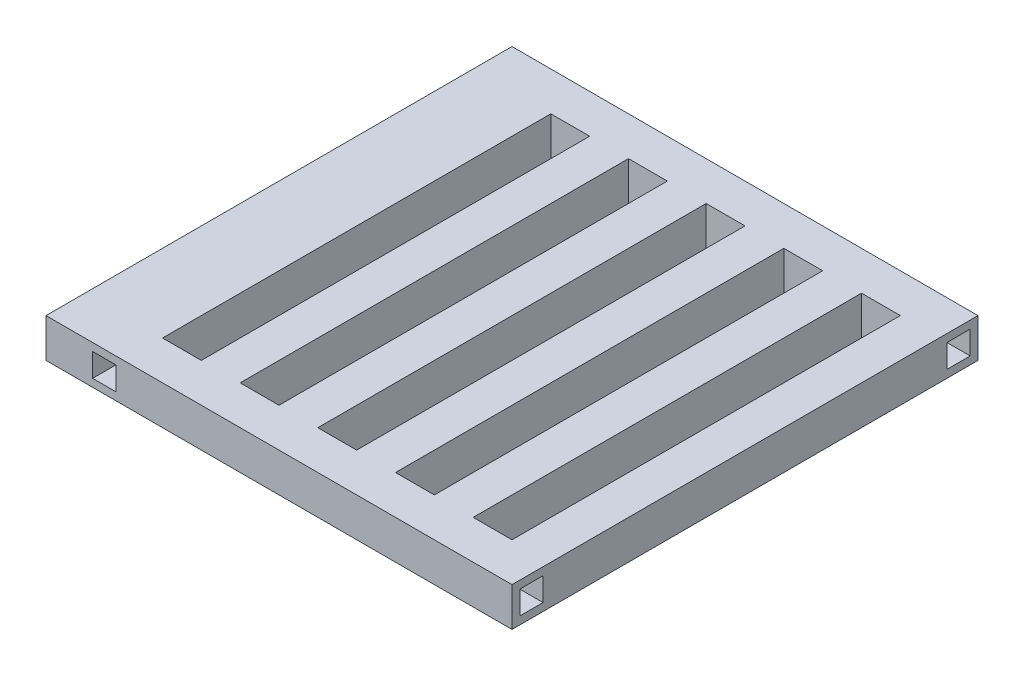
SolidWorks part; units mm, degrees
ref_plane "Front Plane" through (0, 0, 0) normal (0, 0, 1) x (1, 0, 0)
ref_plane "Top Plane" through (0, 0, 0) normal (0, 1, 0) x (1, 0, 0)
ref_plane "Right Plane" through (0, 0, 0) normal (1, 0, 0) x (0, 0, -1)
sketch "Sketch3" plane through (0, 0, 0) normal (0, 1, 0) x (1, 0, 0)
  line L1 (0, 0) -> (-152.4, 0)
  line L2 (0, 0) -> (0, 152.4)
  line L3 (0, 152.4) -> (-152.4, 152.4)
  line L4 (-152.4, 0) -> (-152.4, 152.4)
  dimension "D1" = 152.4
  dimension "D2" = 152.4
extrude "Boss-Extrude1" add sketch "Sketch3" along normal blind 12.7
sketch "Sketch5" plane through (-152.4, 0, 0) normal (-1, 0, 0) x (0, 0, 1)
  line L0 (-149.86, 2.54) -> (-149.86, 10.16)
  line L5 (-149.86, 10.16) -> (-2.54, 10.16)
  line L6 (-2.54, 2.54) -> (-2.54, 10.16)
  line L7 (-149.86, 2.54) -> (-2.54, 2.54)
extrude "Cut-Extrude1" cut sketch "Sketch5" against normal blind 12.7
sketch "Sketch6" plane through (0, 12.7, 0) normal (0, 1, 0) x (1, 0, 0)
  line L0 (-139.7, 12.7) -> (-139.7, 139.7)
  line L5 (-127, 12.7) -> (-127, 139.7)
  line L6 (-114.3, 12.7) -> (-114.3, 139.7)
  line L7 (-101.6, 12.7) -> (-101.6, 139.7)
  line L8 (-88.9, 12.7) -> (-88.9, 139.7)
  line L9 (-76.2, 12.7) -> (-76.2, 139.7)
  line L10 (-63.5, 12.7) -> (-63.5, 139.7)
  line L11 (-50.8, 12.7) -> (-50.8, 139.7)
  line L12 (-38.1, 12.7) -> (-38.1, 139.7)
  line L13 (-25.4, 12.7) -> (-25.4, 139.7)
  line L14 (-12.7, 12.7) -> (-12.7, 139.7)
  line L15 (-12.7, 12.7) -> (-12.7, 139.7)
  line L16 (-12.7, 139.7) -> (-139.7, 139.7)
  line L17 (-12.7, 12.7) -> (-139.7, 12.7)
  line L18 (-127, 0) -> (-127, 152.4) construction
  line L19 (-114.3, 0) -> (-114.3, 152.4) construction
  line L20 (-101.6, 0) -> (-101.6, 152.4) construction
  line L21 (-88.9, 0) -> (-88.9, 152.4) construction
  line L22 (-76.2, 0) -> (-76.2, 152.4) construction
  line L23 (-63.5, 0) -> (-63.5, 152.4) construction
  line L24 (-50.8, 0) -> (-50.8, 152.4) construction
  line L25 (-38.1, 0) -> (-38.1, 152.4) construction
  line L26 (-25.4, 0) -> (-25.4, 152.4) construction
  line L27 (-12.7, 0) -> (-12.7, 152.4) construction
  line L31 (-139.7, 0) -> (-139.7, 152.4) construction
  dimension "D1" = 12.7
  dimension "D2" = 12.7
  dimension "D3" = 12.7
  dimension "D4" = 12.7
  dimension "D5" = 12.7
  dimension "D6" = 12.7
  dimension "D7" = 12.7
  dimension "D8" = 12.7
  dimension "D9" = 12.7
  dimension "D10" = 12.7
extrude "Cut-Extrude3" cut sketch "Sketch6" against normal blind 12.7 contours L17 L6 L16 L5 | L17 L8 L16 L7 | L17 L10 L16 L9 | L17 L12 L16 L11 | L17 L14 L16 L13
sketch "Sketch7" plane through (0, 0, 0) normal (1, 0, 0) x (0, 0, -1)
  line L0 (0, 0) -> (152.4, 0) construction
  line L1 (0, 12.7) -> (12.7, 12.7)
  line L2 (0, 12.7) -> (0, 0)
  line L3 (0, 0) -> (12.7, 0)
  line L4 (12.7, 12.7) -> (12.7, 0)
  dimension "D1" = 12.7
sketch "Sketch8" plane through (0, 0, 0) normal (1, 0, 0) x (0, 0, -1)
  line L15 (149.86, 10.16) -> (142.24, 10.16)
  line L16 (142.24, 2.54) -> (142.24, 10.16)
  line L17 (149.86, 2.54) -> (142.24, 2.54)
  line L18 (149.86, 2.54) -> (149.86, 10.16)
  line L19 (2.54, 2.54) -> (10.16, 2.54)
  line L20 (2.54, 10.16) -> (2.54, 2.54)
  line L21 (10.16, 2.54) -> (10.16, 10.16)
  line L22 (10.16, 10.16) -> (2.54, 10.16)
  line L23 (2.54, 2.54) -> (10.16, 2.54)
  line L24 (2.54, 10.16) -> (2.54, 2.54)
  line L25 (10.16, 2.54) -> (10.16, 10.16)
  line L26 (10.16, 10.16) -> (2.54, 10.16)
  dimension "D2" = 2.54
extrude "Cut-Extrude4" cut sketch "Sketch8" against normal blind 25.4
sketch "Sketch9" plane through (0, 0, 0) normal (0, 0, 1) x (1, 0, 0)
  line L8 (-129.54, 10.16) -> (-129.54, 2.54)
  line L9 (-137.16, 2.54) -> (-129.54, 2.54)
  line L10 (-137.16, 10.16) -> (-137.16, 2.54)
  line L11 (-137.16, 10.16) -> (-129.54, 10.16)
extrude "Cut-Extrude5" cut sketch "Sketch9" against normal blind 25.4
sketch "Sketch10" plane through (0, 0, -152.4) normal (0, 0, -1) x (-1, 0, 0)
  line L11 (137.16, 2.54) -> (137.16, 10.16)
  line L12 (137.16, 10.16) -> (129.6511, 10.16)
  line L13 (129.6511, 2.54) -> (129.6511, 10.16)
  line L14 (137.16, 2.54) -> (129.6511, 2.54)
extrude "Cut-Extrude6" cut sketch "Sketch10" against normal blind 25.4
